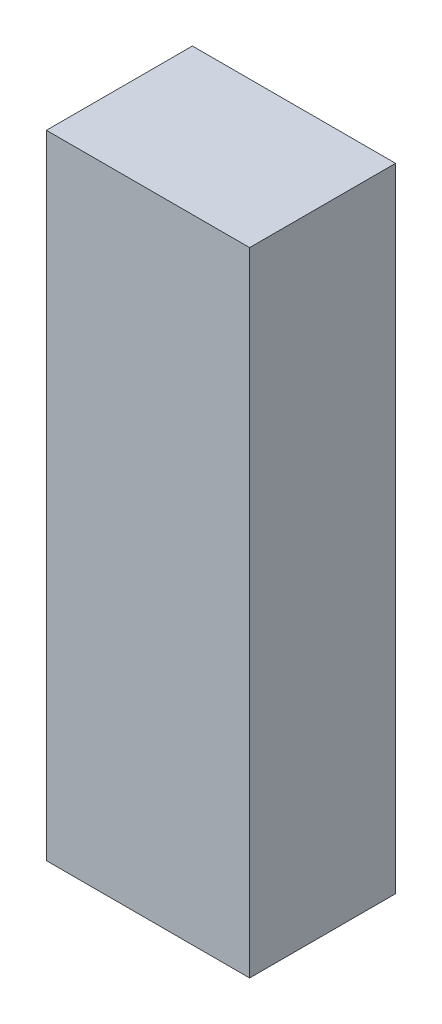
SolidWorks part; units mm, degrees
ref_plane "Front Plane" through (0, 0, 0) normal (0, 0, 1) x (1, 0, 0)
ref_plane "Top Plane" through (0, 0, 0) normal (0, 1, 0) x (1, 0, 0)
ref_plane "Right Plane" through (0, 0, 0) normal (1, 0, 0) x (0, 0, -1)
sketch "Sketch1" plane through (0, 0, 0) normal (0, 0, 1) x (1, 0, 0)
  line L1 (33.0629, 22.9785) -> (-2.4371, 22.9785)
  line L2 (33.0629, 22.9785) -> (33.0629, 133.4785)
  line L3 (33.0629, 133.4785) -> (-2.4371, 133.4785)
  line L4 (-2.4371, 22.9785) -> (-2.4371, 133.4785)
  line L5 (33.0629, 22.9785) -> (-2.4371, 133.4785) construction
  line L6 (33.0629, 133.4785) -> (-2.4371, 22.9785) construction
  point P0 (15.3129, 78.2285)
  dimension "D1" = 110.5
  dimension "D2" = 35.5
extrude "Boss-Extrude1" add sketch "Sketch1" along normal blind 25.5
